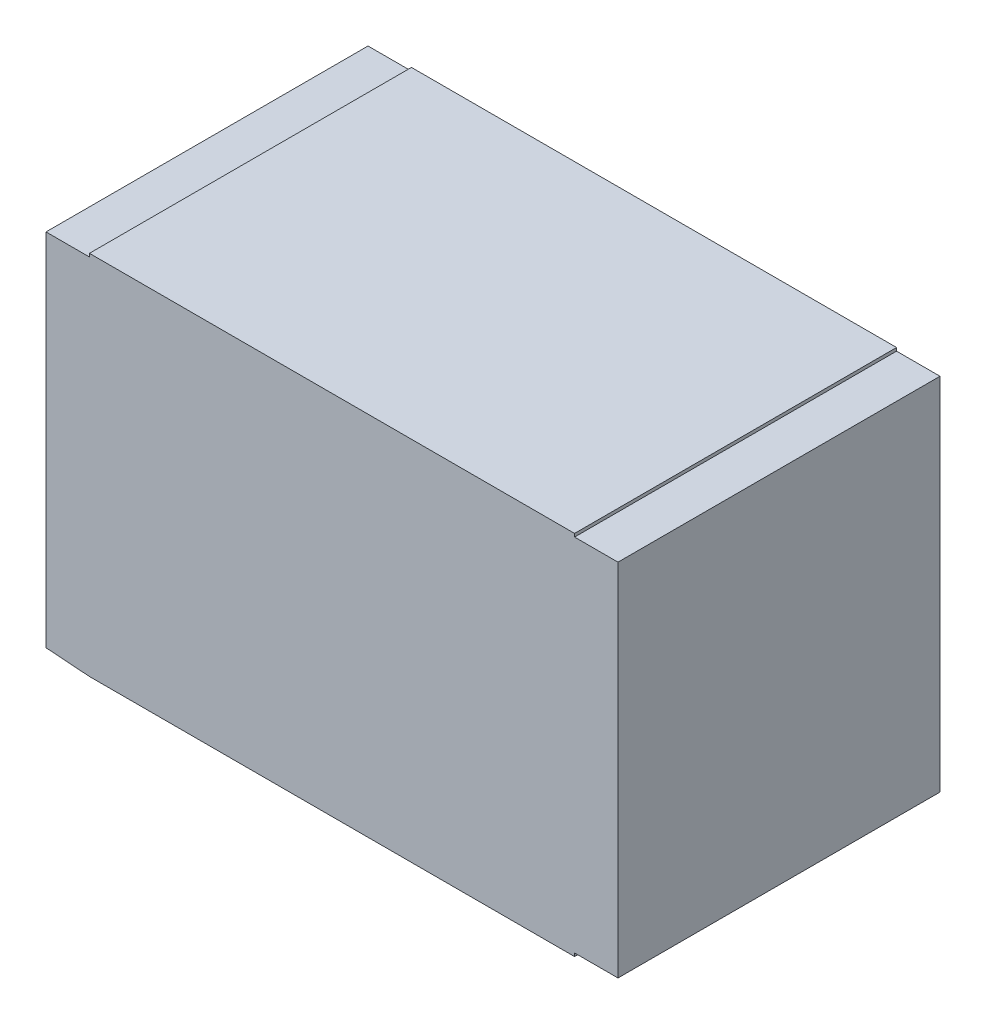
SolidWorks part; units mm, degrees
ref_plane "前视基准面" through (0, 0, 0) normal (0, 0, 1) x (1, 0, 0)
ref_plane "上视基准面" through (0, 0, 0) normal (0, 1, 0) x (1, 0, 0)
ref_plane "右视基准面" through (0, 0, 0) normal (1, 0, 0) x (0, 0, -1)
sketch "草图1" plane through (0, 0, 0) normal (0, 0, 1) x (1, 0, 0)
  line L0 (-1.35, 0.85) -> (-1.145, 0.85)
  line L1 (-1.145, 0.85) -> (-1.145, 0.865)
  line L2 (-1.145, 0.865) -> (1.145, 0.865)
  line L3 (1.145, 0.865) -> (1.145, 0.85)
  line L4 (1.145, 0.85) -> (1.35, 0.85)
  line L5 (1.35, 0.85) -> (1.35, -0.85)
  line L6 (1.35, -0.85) -> (1.145, -0.85)
  line L7 (1.145, -0.85) -> (1.145, -0.865)
  line L8 (1.145, -0.865) -> (-1.145, -0.865)
  line L9 (-1.145, -0.865) -> (-1.35, -0.85)
  line L10 (-1.35, -0.85) -> (-1.35, 0.85)
extrude "Component_Outline" add sketch "草图1" along normal blind 1.52 separate body
sketch3d "3D草图1"
  line L0 (0, 0, 0) -> (1, 0, 0)
  line L1 (0, 0, 0) -> (0, 1, 0)
  line L2 (0, 0, 0) -> (0, 0, 1)
  point P0 (0, 0, 0)
